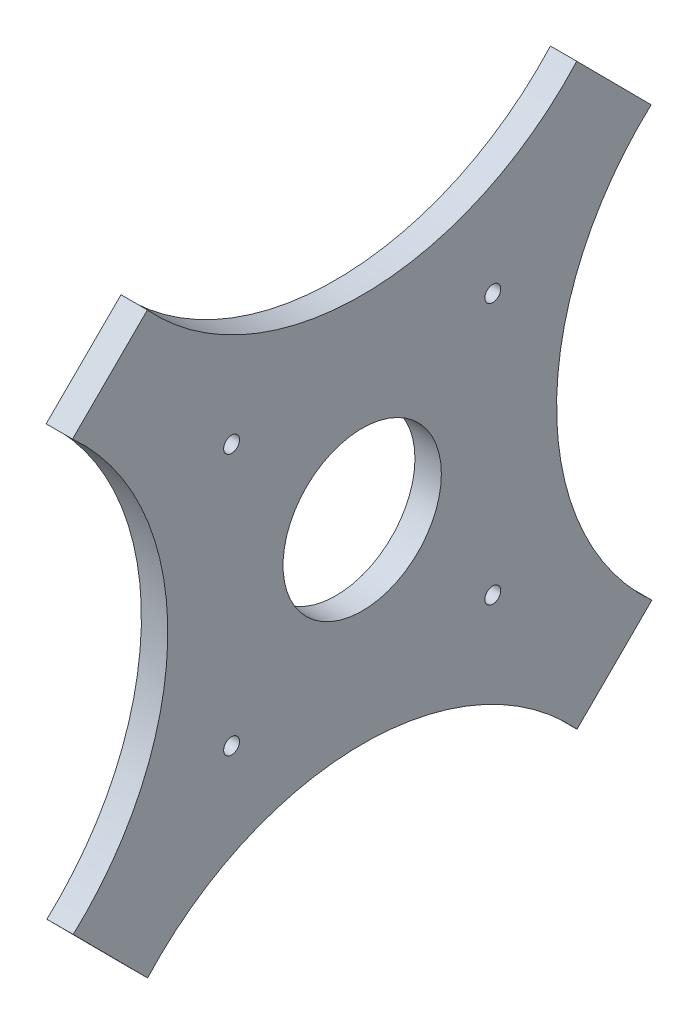
SolidWorks part; units mm, degrees
ref_plane "前视基准面" through (0, 0, 0) normal (0, 0, 1) x (1, 0, 0)
ref_plane "上视基准面" through (0, 0, 0) normal (0, 1, 0) x (1, 0, 0)
ref_plane "右视基准面" through (0, 0, 0) normal (1, 0, 0) x (0, 0, -1)
sketch "草图1" plane through (0, 0, 0) normal (1, 0, 0) x (0, 0, -1)
  line L0 (-107.5623, 0) -> (107.5623, 0) construction
  line L1 (0, 73.2239) -> (0, -73.2239) construction
  line L2 (-54.8912, 40.6635) -> (-40.6997, 54.7561)
  line L7 (-60, 60) -> (60, -60) construction
  line L8 (-60, -60) -> (60, 60) construction
  line L9 (40.6635, 54.8912) -> (54.7561, 40.6997)
  line L10 (-54.7561, -40.6997) -> (-40.6635, -54.8912)
  line L11 (54.8912, -40.6635) -> (40.6997, -54.7561)
  arc A0 (-54.8912, 40.6635) -> (-54.7561, -40.6997) centre (-91.8371, -0.0795) cw
  arc A1 (40.6635, 54.8912) -> (-40.6997, 54.7561) centre (-0.0795, 91.8371) cw
  arc A2 (54.8912, -40.6635) -> (54.7561, 40.6997) centre (91.8371, 0.0795) cw
  arc A3 (-40.6635, -54.8912) -> (40.6997, -54.7561) centre (0.0795, -91.8371) cw
  circle A4 centre (0, 0) radius 15
  circle A6 centre (0, 0) radius 35 construction
  circle A7 centre (24.7487, 24.7487) radius 1.5
  circle A8 centre (24.7487, -24.7487) radius 1.5
  circle A9 centre (-24.7487, -24.7487) radius 1.5
  circle A10 centre (-24.7487, 24.7487) radius 1.5
  point P0 (0, 0)
  point P4 (0, 0)
  point P8 (0, 0)
  point P34 (0, 0)
  point P39 (0, 0)
  dimension "D3" = 55
  dimension "D8" = 30
  dimension "D10" = 70
  dimension "D11" = 3
  dimension "D1" = 120
  dimension "D9" = 20
  dimension "D2" = 4
  dimension "D12" = 4
extrude "凸台-拉伸1" add sketch "草图1" along normal blind 5
